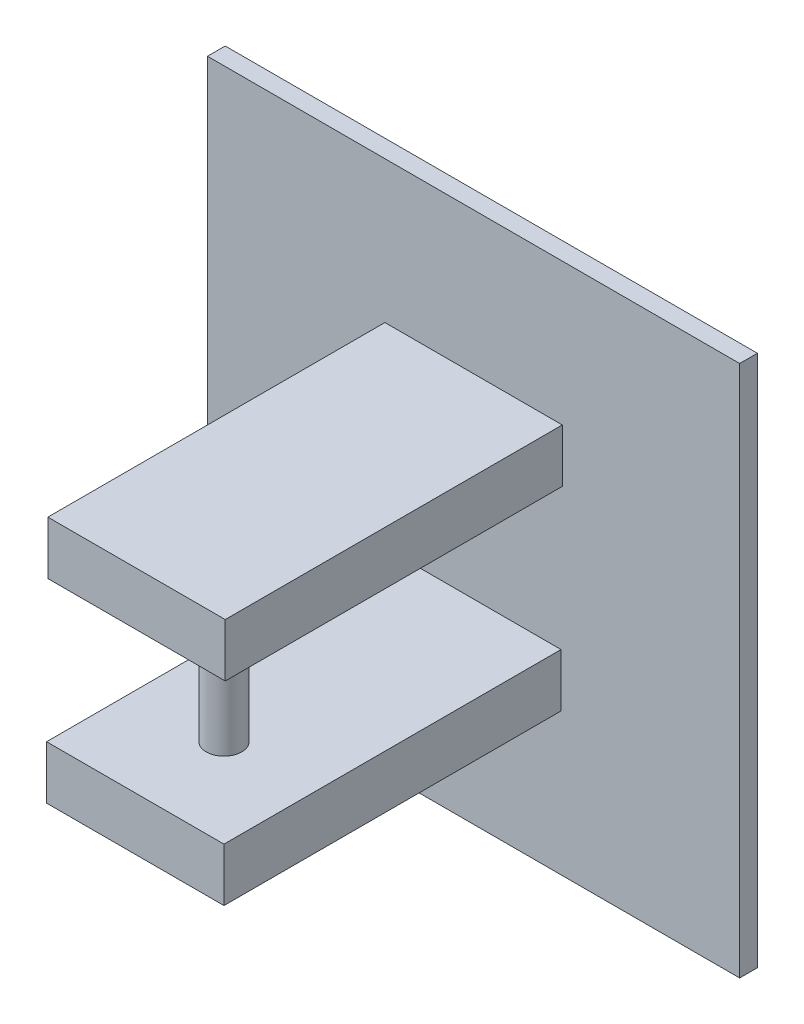
SolidWorks part; units mm, degrees
ref_plane "Piano frontale" through (0, 0, 0) normal (0, 0, 1) x (1, 0, 0)
ref_plane "Piano superiore" through (0, 0, 0) normal (0, 1, 0) x (1, 0, 0)
ref_plane "Piano destro" through (0, 0, 0) normal (1, 0, 0) x (0, 0, -1)
sketch "Schizzo2" plane through (0, 0, 0) normal (0, 0, 1) x (1, 0, 0)
  line L0 (0, 0) -> (150, 0)
  line L1 (150, 0) -> (150, 150)
  line L2 (150, 150) -> (0, 150)
  line L3 (0, 150) -> (0, 0)
  dimension "D1" = 150
  dimension "D2" = 150
extrude "Estrusione-Estrusione1" add sketch "Schizzo2" against normal blind 5 contours L0 L1 L2 L3
sketch "Schizzo3" plane through (0, 0, 0) normal (0, 0, 1) x (1, 0, 0)
  line L0 (49.643, 55) -> (49.643, 40)
  line L1 (49.643, 40) -> (99.643, 40)
  line L2 (99.643, 40) -> (99.643, 55)
  line L3 (99.643, 55) -> (49.643, 55)
  line L4 (50, 110) -> (50, 95)
  line L5 (50, 95) -> (100, 95)
  line L6 (100, 95) -> (100, 110)
  line L7 (100, 110) -> (50, 110)
  line L8 (0, 150) -> (0, 0) construction
  line L9 (0, 0) -> (150, 0) construction
  dimension "D1" = 50
  dimension "D2" = 50
  dimension "D3" = 50
  dimension "D4" = 49.643
  dimension "D5" = 15
  dimension "D6" = 15
  dimension "D7" = 15
  dimension "D8" = 40
  dimension "D9" = 40
extrude "Estrusione-Estrusione2" add sketch "Schizzo3" along normal blind 95
sketch "Schizzo6" plane through (0, 40, 0) normal (0, -1, 0) x (1, 0, 0)
  line L0 (49.643, 70) -> (99.643, 70) construction
  line L1 (49.643, 95) -> (49.643, 0) construction
  line L2 (99.643, 95) -> (99.643, 0) construction
  line L4 (74.643, 95) -> (74.643, 62.3216) construction
  line L5 (49.643, 95) -> (99.643, 95) construction
  circle A0 centre (74.643, 70) radius 5
  dimension "D3" = 10
  dimension "D1" = 25
  dimension "D2" = 25
extrude "Estrusione-Estrusione3" add sketch "Schizzo6" against normal blind 61.6301 contours A0
